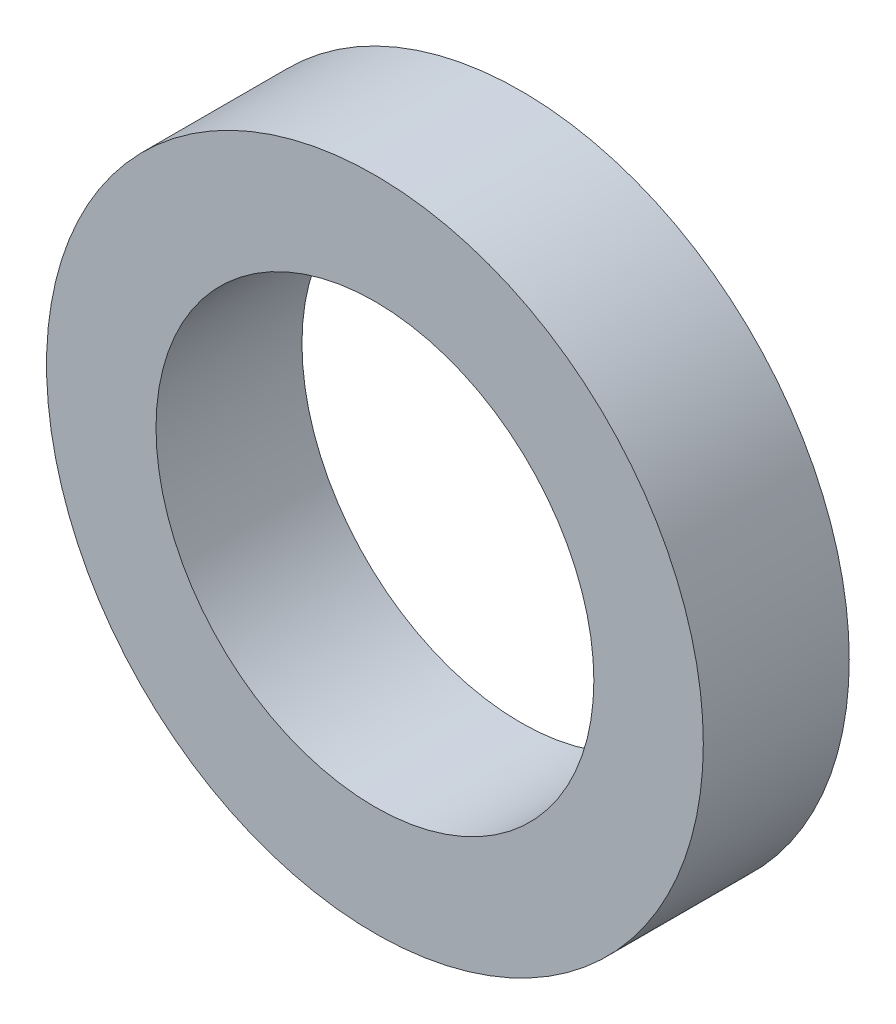
SolidWorks part; units mm, degrees
ref_plane "前视基准面" through (0, 0, 0) normal (0, 0, 1) x (1, 0, 0)
ref_plane "上视基准面" through (0, 0, 0) normal (0, 1, 0) x (1, 0, 0)
ref_plane "右视基准面" through (0, 0, 0) normal (1, 0, 0) x (0, 0, -1)
other "Configuration Table"
sketch "草图1" plane through (0, 0, 0) normal (0, 0, 1) x (1, 0, 0)
  circle A0 centre (0, 0) radius 6
  circle A1 centre (0, 0) radius 9
  dimension "D1" = 18
  dimension "D2" = 12
extrude "凸台-拉伸1" add sketch "草图1" along normal blind 4
